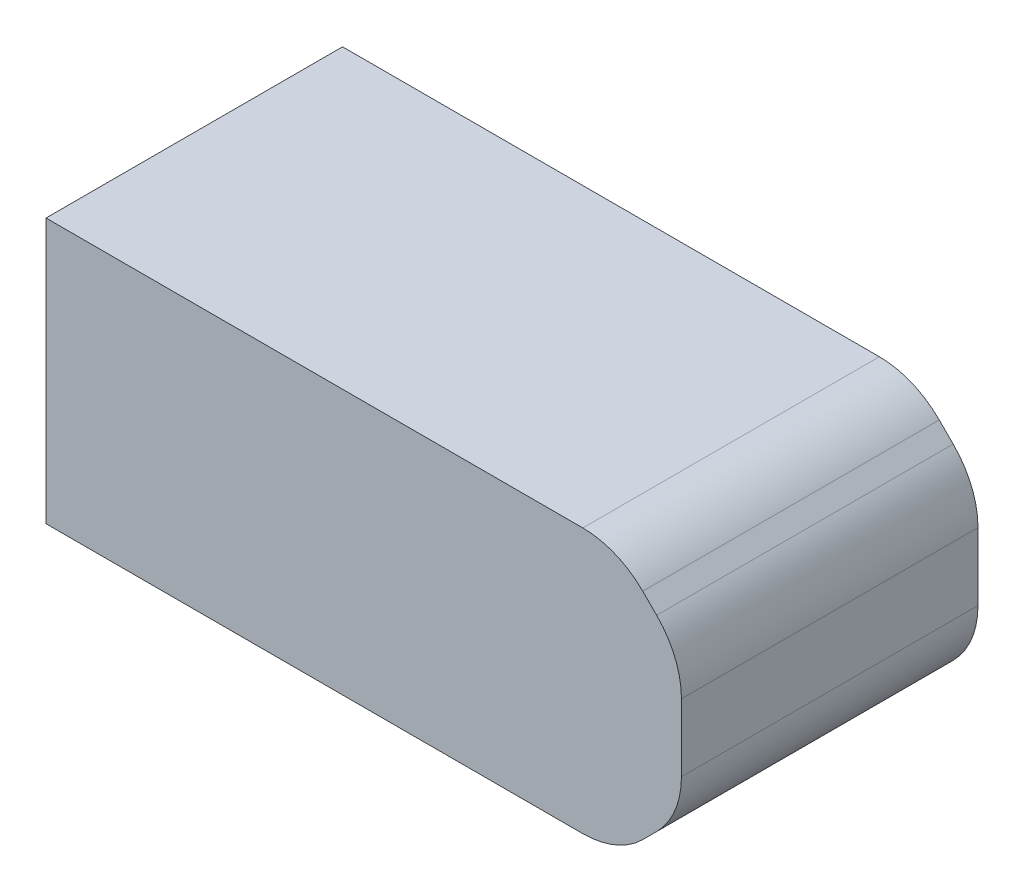
SolidWorks part; units mm, degrees
ref_plane "Front Plane" through (0, 0, 0) normal (0, 0, 1) x (1, 0, 0)
ref_plane "Top Plane" through (0, 0, 0) normal (0, 1, 0) x (1, 0, 0)
ref_plane "Right Plane" through (0, 0, 0) normal (1, 0, 0) x (0, 0, -1)
sketch "Sketch2" plane through (0, 0, 0) normal (0, 1, 0) x (1, 0, 0)
  line L1 (-30, 14) -> (30, 14)
  line L2 (-30, 14) -> (-30, -14)
  line L3 (-30, -14) -> (30, -14)
  line L4 (30, 14) -> (30, -14)
  line L5 (-30, 14) -> (30, -14) construction
  line L6 (-30, -14) -> (30, 14) construction
  point P0 (0, 0)
  dimension "D1" = 28
  dimension "D2" = 60
extrude "Boss-Extrude1" add sketch "Sketch2" along normal blind 25
chamfer "Chamfer1" distance 6 angle 45 2 edges at (30, 0, 0) (30, 25, 0)
fillet "Fillet1" radius 8 2 edges at (30, 19, 0) (30, 6, 0)
fillet "Fillet2" radius 8 2 edges at (24, 0, 0) (24, 25, 0)
